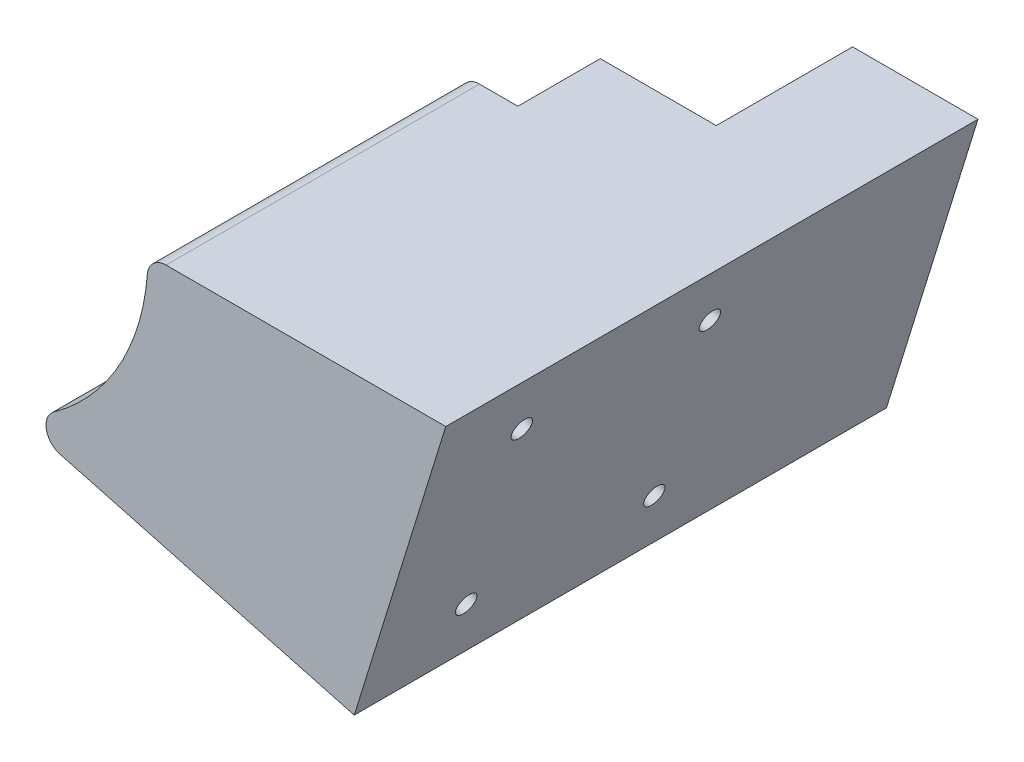
SolidWorks part; units mm, degrees
ref_plane "Front Plane" through (0, 0, 0) normal (0, 0, 1) x (1, 0, 0)
ref_plane "Top Plane" through (0, 0, 0) normal (0, 1, 0) x (1, 0, 0)
ref_plane "Right Plane" through (0, 0, 0) normal (1, 0, 0) x (0, 0, -1)
sketch "Sketch1" plane through (0, 0, 0) normal (0, 0, 1) x (1, 0, 0)
  line L0 (36, 0) -> (63.5, 0)
  line L1 (15, -61.7029) -> (15, -32.7261)
  arc A0 (36, 0) -> (15, -32.7261) centre (0, 0) cw
  arc A1 (63.5, 0) -> (15, -61.7029) centre (0, 0) cw
  dimension "D1" = 36
  dimension "D2" = 63.5
  dimension "D3" = 15
extrude "Boss-Extrude1" add sketch "Sketch1" along normal blind 50
sketch "Sketch2" plane through (0, 0, 0) normal (0, 0, -1) x (-1, 0, 0)
  line L0 (-63.5, 0) -> (-36, 0) construction
  line L1 (-15, -32.7261) -> (-15, -61.7029) construction
  line L4 (-45, 0) -> (-63.5, 0)
  line L5 (-15, -61.7029) -> (-15, -42.4264)
  arc A0 (-45, 0) -> (-15, -42.4264) centre (0, 0) ccw
  arc A2 (-63.5, 0) -> (-15, -61.7029) centre (0, 0) ccw
  dimension "D1" = 45
extrude "Boss-Extrude2" add sketch "Sketch2" along normal blind 13.15
sketch "Sketch3" plane through (0, 0, -13.15) normal (0, 0, -1) x (-1, 0, 0)
  line L0 (-63.5, 0) -> (-83.5, 0)
  line L1 (-15, -61.7029) -> (-15, -82.1416)
  arc A0 (-83.5, 0) -> (-15, -82.1416) centre (0, 0) ccw
  arc A1 (-36, 0) -> (-15, -32.7261) centre (0, 0) ccw construction
  arc A2 (-36, 0) -> (-15, -32.7261) centre (0, 0) ccw construction
  arc A3 (-63.5, 0) -> (-15, -61.7029) centre (0, 0) ccw construction
  arc A4 (-63.5, 0) -> (-15, -61.7029) centre (0, 0) ccw
  dimension "D1" = 20
extrude "Boss-Extrude3" add sketch "Sketch3" along normal blind 21.75 and the other way up to surface (63.15 mm away) other way up to face at (36.2431, -26.4745, 50)
sketch "Sketch4" plane through (0, 0, 50) normal (0, 0, 1) x (1, 0, 0)
  line L0 (15, -32.7261) -> (68.901, -47.1689)
  line L1 (15, -32.7261) -> (15, -82.1416)
  line L2 (83.5, 0) -> (36, 0) construction
  arc A0 (15, -82.1416) -> (83.5, 0) centre (0, 0) ccw construction
  arc A1 (15, -82.1416) -> (68.901, -47.1689) centre (0, 0) ccw
  dimension "D1" = 15
extrude "Cut-Extrude1" cut sketch "Sketch4" against normal through all
fillet "Fillet1" radius 3 2 edges at (36, 0, 25) (15, -32.7261, 25)
sketch "Sketch5" plane through (0, 0, 50) normal (0, 0, 1) x (1, 0, 0)
  line L0 (83.5, 0) -> (68.901, -47.1689)
  arc A0 (83.5, 0) -> (68.901, -47.1689) centre (0, 0) cw
extrude "Cut-Extrude2" cut sketch "Sketch5" against normal through all
hole_wizard "Tap Drill for M4x0.7 Tap1" positions "Sketch6" profile "Sketch8" hole size "M4x0.7" standard "ANSI Metric"
sketch "Sketch6" plane through (76.2005, -23.5844, 0) normal (0.9553, -0.2957, 0) x (0, 0, -1)
  point P0 (-35, 15)
  point P2 (-35, -15)
  point P4 (-5, 15)
  point P6 (-5, -15)
  dimension "D1" = 15
  dimension "D2" = 30
  dimension "D3" = 5
  dimension "D4" = 30
sketch "Sketch8" plane through (80.6355, -9.2551, 35) normal (0, 0, 1) x (0.2957, 0.9553, 0)
  line L0 (0, 0) -> (0, 10.9914)
  line L1 (0, 10.9914) -> (1.65, 10)
  line L2 (1.65, 10) -> (1.65, 0)
  line L5 (1.65, 0) -> (0, 0)
  line L10 (0, 10.9914) -> (-1.65, 10) construction
  line L11 (0, -6.35) -> (0, 107.95) construction
  dimension "Hole Dia." = 3.3
  dimension "Hole Depth" = 10
  dimension "Drill Angle" = 118
